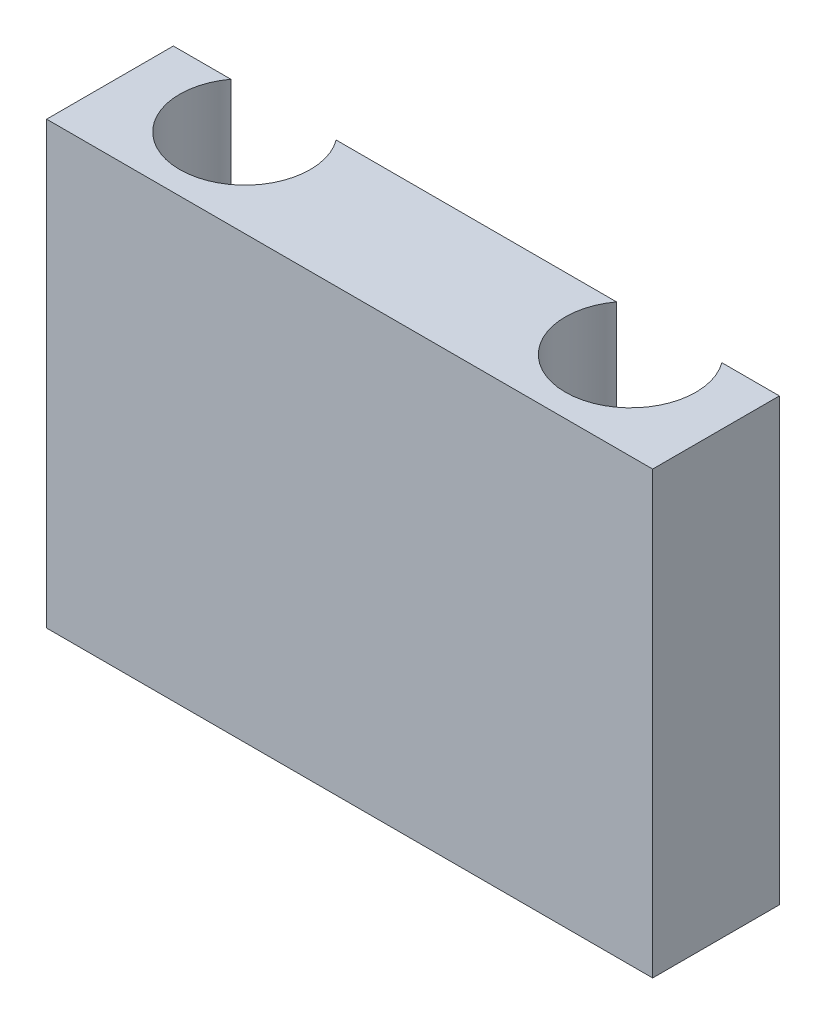
SolidWorks part; units mm, degrees
ref_plane "Front Plane" through (0, 0, 0) normal (0, 0, 1) x (1, 0, 0)
ref_plane "Top Plane" through (0, 0, 0) normal (0, 1, 0) x (1, 0, 0)
ref_plane "Right Plane" through (0, 0, 0) normal (1, 0, 0) x (0, 0, -1)
sketch "Sketch2" plane through (0, 0, 0) normal (0, 0, 1) x (1, 0, 0)
  line L1 (0, 0) -> (110, 0)
  line L2 (0, 0) -> (0, 80)
  line L3 (0, 80) -> (110, 80)
  line L4 (110, 0) -> (110, 80)
  dimension "D1" = 80
  dimension "D2" = 110
extrude "Boss-Extrude1" add sketch "Sketch2" along normal blind 23
sketch "Sketch3" plane through (0, 80, 0) normal (0, 1, 0) x (1, 0, 0)
  line L0 (0, -7) -> (110, -7) construction
  line L1 (0, 0) -> (110, 0) construction
  line L2 (0, 0) -> (0, -23) construction
  line L3 (0, -23) -> (110, -23) construction
  line L4 (110, 0) -> (110, -23) construction
  line L5 (55, 0) -> (55, -48.0949) construction
  circle A0 centre (20, -7) radius 9.1
  circle A1 centre (90, -7) radius 9.1
  dimension "D1" = 18.2
  dimension "D3" = 70
  dimension "D2" = 7
extrude "Thread extrude" cut sketch "Sketch3" against normal blind 45 contours A1 | A0
sketch "Sketch6" plane through (0, 80, 0) normal (0, 1, 0) x (1, 0, 0)
  arc A0 (84.1854, 0) -> (95.8146, 0) centre (90, -7) ccw construction
  arc A2 (14.1854, 0) -> (25.8146, 0) centre (20, -7) ccw construction
  arc A4 (84.1854, 0) -> (95.8146, 0) centre (90, -7) ccw construction
  arc A6 (14.1854, 0) -> (25.8146, 0) centre (20, -7) ccw construction
  circle A8 centre (20, -7) radius 8.4
  circle A9 centre (90, -7) radius 8.4
  dimension "D1" = 16.8
sketch "Sketch5" plane through (0, 80, 0) normal (0, 1, 0) x (1, 0, 0)
  arc A0 (84.1854, 0) -> (95.8146, 0) centre (90, -7) ccw construction
  arc A1 (14.1854, 0) -> (25.8146, 0) centre (20, -7) ccw construction
  arc A2 (84.1854, 0) -> (95.8146, 0) centre (90, -7) ccw construction
  arc A3 (14.1854, 0) -> (25.8146, 0) centre (20, -7) ccw construction
  circle A4 centre (20, -7) radius 11.85
  circle A5 centre (90, -7) radius 11.85
  dimension "D1" = 23.7
extrude "Nut extrude" cut sketch "Sketch5" against normal blind 17
extrude "minor dianeter extrude" cut sketch "Sketch6" against normal blind 64
sketch "Sketch4" plane through (0, 80, 0) normal (0, 1, 0) x (1, 0, 0)
  line L0 (30.6184, -7) -> (90, -7) construction
  line L1 (17, -7) -> (17, 0)
  line L2 (14.1854, 0) -> (15.3567, 0) construction
  line L3 (23, -7) -> (23, 0)
  line L4 (87, -7) -> (87, 0)
  line L5 (84.1854, 0) -> (85.3567, 0) construction
  line L6 (93, -7) -> (93, 0)
  line L7 (17, 0) -> (23, 0)
  line L8 (93, 0) -> (87, 0)
  arc A0 (84.1854, 0) -> (95.8146, 0) centre (90, -7) ccw construction
  arc A1 (14.1854, 0) -> (25.8146, 0) centre (20, -7) ccw construction
  arc A2 (84.1854, 0) -> (95.8146, 0) centre (90, -7) ccw construction
  arc A3 (14.1854, 0) -> (25.8146, 0) centre (20, -7) ccw construction
  arc A4 (17, -7) -> (23, -7) centre (20, -7) ccw
  arc A5 (87, -7) -> (93, -7) centre (90, -7) ccw
  dimension "D1" = 3
extrude "Cable extrude" cut sketch "Sketch4" against normal through all
